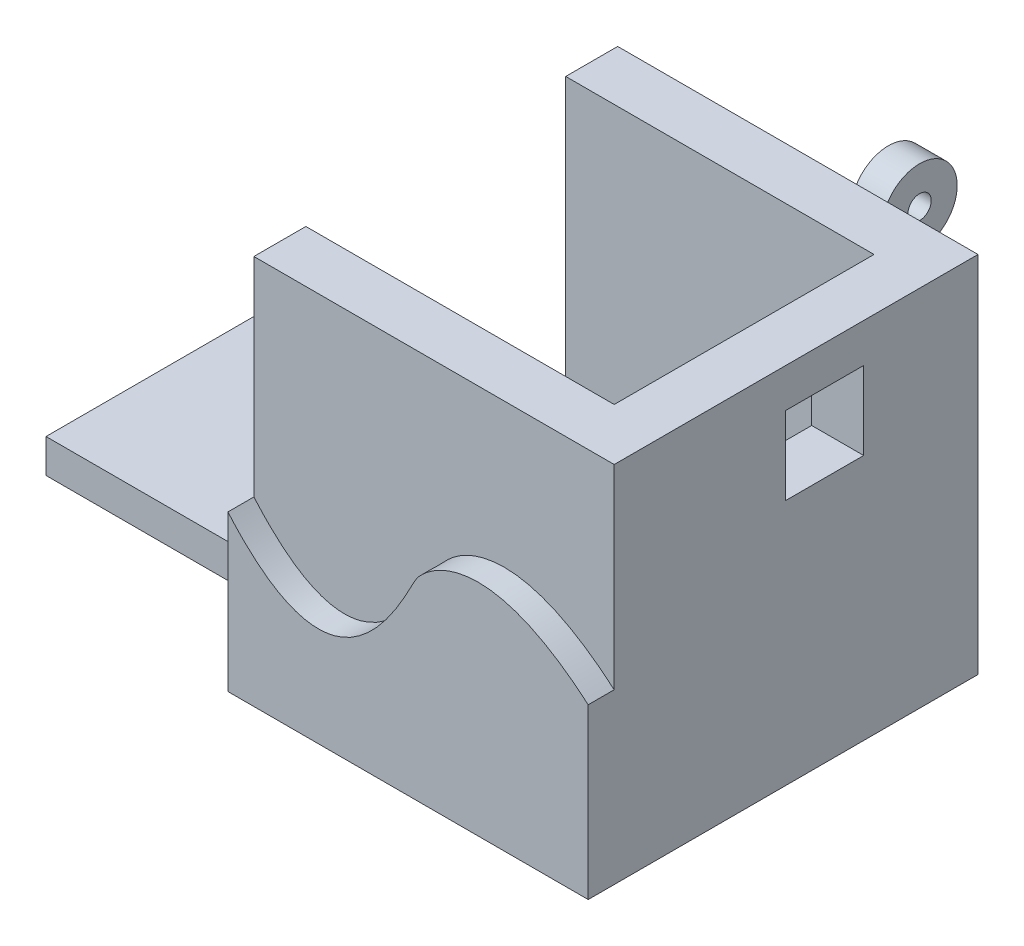
SolidWorks part; units mm, degrees
ref_plane "前基準面" through (0, 0, 0) normal (0, 0, 1) x (1, 0, 0)
ref_plane "上基準面" through (0, 0, 0) normal (0, 1, 0) x (1, 0, 0)
ref_plane "右基準面" through (0, 0, 0) normal (1, 0, 0) x (0, 0, -1)
sketch "草圖1" plane through (0, 0, 0) normal (0, 1, 0) x (1, 0, 0)
  line L1 (-69.33, 70) -> (69.33, 70)
  line L2 (-69.33, 70) -> (-69.33, -70)
  line L3 (-69.33, -70) -> (69.33, -70)
  line L4 (69.33, 70) -> (69.33, -70)
  line L5 (-69.33, 70) -> (69.33, -70) construction
  line L6 (-69.33, -70) -> (69.33, 70) construction
  point P0 (0, 0)
  dimension "D1" = 138.66
  dimension "D2" = 140
extrude "填料-伸長1" add sketch "草圖1" along normal blind 140
sketch "草圖2" plane through (0, 140, 0) normal (0, 1, 0) x (1, 0, 0)
  line L0 (-69.33, 70) -> (-69.33, -70) construction
  line L1 (-69.33, 50) -> (49.33, 50)
  line L2 (-69.33, 50) -> (-69.33, -50)
  line L3 (-69.33, -50) -> (49.33, -50)
  line L4 (49.33, 50) -> (49.33, -50)
  line L5 (69.33, 70) -> (-69.33, 70) construction
  line L6 (69.33, -70) -> (69.33, 70) construction
  line L7 (-69.33, -70) -> (69.33, -70) construction
  dimension "D1" = 20
  dimension "D2" = 20
  dimension "D3" = 20
extrude "除料-伸長1" cut sketch "草圖2" against normal blind 110
sketch "草圖3" plane through (-69.33, 0, 0) normal (-1, 0, 0) x (0, 0, 1)
  line L0 (50, 30) -> (-50, 30) construction
  line L1 (-50, 20) -> (50, 20)
  line L2 (-50, 20) -> (-50, 7)
  line L3 (-50, 7) -> (50, 7)
  line L4 (50, 20) -> (50, 7)
  line L5 (-70, 0) -> (70, 0) construction
  line L6 (-70, 140) -> (-70, 0) construction
  line L7 (70, 140) -> (70, 0) construction
  dimension "D1" = 10
  dimension "D2" = 7
  dimension "D3" = 20
  dimension "D4" = 20
extrude "填料-伸長2" add sketch "草圖3" along normal blind 100
sketch "草圖4" plane through (0, 20, 0) normal (0, 1, 0) x (1, 0, 0)
  line L0 (-69.33, 0) -> (-89.33, 0) construction
  line L1 (-69.33, -50) -> (-69.33, 50) construction
  circle A0 centre (-89.33, 0) radius 3
  dimension "D2" = 6
  dimension "D1" = 20
extrude "除料-伸長3" cut sketch "草圖4" against normal through all
sketch "草圖5" plane through (0, 0, -70) normal (0, 0, -1) x (-1, 0, 0)
  line L0 (-69.33, 140) -> (-69.33, 0) construction
  line L1 (-34.33, 132) -> (-22.33, 132)
  line L2 (-34.33, 132) -> (-34.33, 120)
  line L3 (-34.33, 120) -> (-22.33, 120)
  line L4 (-22.33, 132) -> (-22.33, 120)
  line L5 (-69.33, 140) -> (69.33, 140) construction
  dimension "D1" = 35
  dimension "D2" = 12
  dimension "D3" = 12
  dimension "D4" = 8
extrude "填料-伸長3" add sketch "草圖5" along normal blind 10
sketch "草圖6" plane through (34.33, 0, 0) normal (1, 0, 0) x (0, 0, -1)
  line L0 (80, 132) -> (82.5, 132) construction
  circle A0 centre (82.5, 132) radius 4.4909
  dimension "D1" = 2.5
extrude "伸長-薄件2" add sketch "草圖6" against normal blind 12 thin
sketch "草圖7" plane through (34.33, 0, 0) normal (1, 0, 0) x (0, 0, -1)
  circle A0 centre (82.5, 132) radius 4.4909
extrude "除料-伸長4" cut sketch "草圖7" against normal through all
sketch "草圖8" plane through (0, 0, 70) normal (0, 0, 1) x (1, 0, 0)
  line L0 (-69.33, 140) -> (-69.33, 59.86) construction
  line L1 (-69.33, 140) -> (-69.33, 0) construction
  line L2 (69.33, 140) -> (69.33, 0) construction
  line L3 (69.33, 64.9321) -> (69.33, 0)
  line L4 (69.33, 0) -> (-69.33, 0)
  line L5 (-69.33, 0) -> (-69.33, 59.86)
  spline S0 degree 3 poles (-69.33, 59.86) (-30.3243, 14.7238) (-7.3704, 53.3025) (5.6625, 78.8871) (32.0758, 96.8762) (69.33, 64.9321) knots 0 0 0 0 0.759135 0.799849 1 1 1 1
extrude "填料-伸長4" add sketch "草圖8" along normal blind 10
sketch "草圖10" plane through (49.33, 0, 0) normal (-1, 0, 0) x (0, 0, 1)
  line L0 (27.4661, 30) -> (27.4661, 95) construction
  line L1 (50, 30) -> (-50, 30) construction
  line L2 (50, 95) -> (4, 95) construction
  line L3 (50, 30) -> (50, 140) construction
  line L5 (4, 95) -> (-26, 95)
  line L6 (4, 95) -> (4, 125)
  line L7 (4, 125) -> (-26, 125)
  line L8 (-26, 95) -> (-26, 125)
  dimension "D1" = 30
  dimension "D2" = 30
extrude "除料-伸長6" cut sketch "草圖10" against normal blind 40
